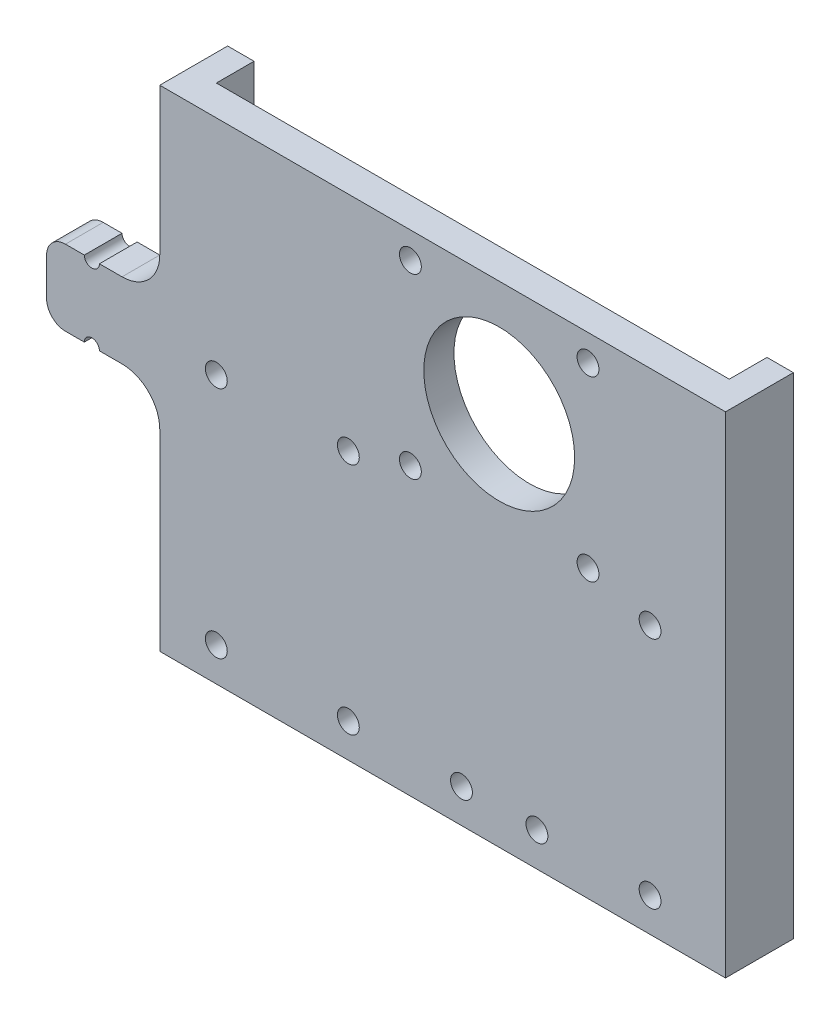
SolidWorks part; units mm, degrees
material "Acrylic (Medium-high impact)"
ref_plane "Front Plane" through (0, 0, 0) normal (0, 0, 1) x (1, 0, 0)
ref_plane "Top Plane" through (0, 0, 0) normal (0, 1, 0) x (1, 0, 0)
ref_plane "Right Plane" through (0, 0, 0) normal (1, 0, 0) x (0, 0, -1)
sketch "Sketch1" plane through (0, 0, 0) normal (0, 0, 1) x (1, 0, 0)
  line L1 (-50, 65) -> (50, 65)
  line L2 (-50, 65) -> (-50, -65)
  line L3 (-50, -65) -> (50, -65)
  line L4 (50, 65) -> (50, -65)
  line L5 (-50, 65) -> (50, -65) construction
  line L6 (-50, -65) -> (50, 65) construction
  point P0 (0, 0)
  dimension "D1" = 100
  dimension "D2" = 130
extrude "Boss-Extrude1" add sketch "Sketch1" along normal blind 8
sketch "Sketch4" plane through (0, 0, 8) normal (0, 0, 1) x (1, 0, 0)
  line L0 (-50, -65) -> (50, -65) construction
  line L1 (50, 65) -> (-50, 65) construction
  line L2 (-50, 65) -> (-50, -65) construction
  line L3 (50, -65) -> (50, 65) construction
  point P0 (-40, 6)
  point P2 (40, 6)
  point P4 (-40, -56)
  point P6 (40, -56)
  point P14 (-23.55, 58)
  point P16 (23.55, 58)
  point P17 (-23.55, 10.9)
  point P19 (23.55, 10.9)
  point P43 (-10, -56)
  point P46 (10, -56)
  dimension "D1" = 62
  dimension "D3" = 9
  dimension "D6" = 47.1
  dimension "D7" = 7
  dimension "D8" = 47.1
  dimension "D9" = 23.55
  dimension "D2" = 10
  dimension "D4" = 10
  dimension "D5" = 20
  dimension "D10" = 10
hole_wizard "M5 Clearance Hole1" positions "Sketch4" profile "Sketch3" hole size "M5" standard "ISO" end condition through all
sketch "Sketch3" plane through (-40, 6, 8) normal (1, 0, 0) x (0, -1, 0)
  line L0 (0, 0) -> (0, 8)
  line L1 (0, 8) -> (2.9, 8)
  line L2 (2.9, 8) -> (2.9, 0)
  line L5 (2.9, 0) -> (0, 0)
  line L11 (0, -6.35) -> (0, 107.95) construction
  dimension "Thru Hole Dia." = 5.8
  dimension "Thru Hole Depth" = 8
sketch "Sketch6" plane through (0, 0, 8) normal (0, 0, 1) x (1, 0, 0)
  circle A0 centre (0, 34.5) radius 20
  circle A1 centre (-23.55, 58) radius 2.9 construction
  dimension "D1" = 40
  dimension "D2" = 23.5
extrude "Cut-Extrude1" cut sketch "Sketch6" against normal blind 10
sketch "Sketch9" plane through (0, 0, 8) normal (0, 0, 1) x (1, 0, 0)
  line L0 (-50, -65) -> (50, -65) construction
  line L1 (-50, 65) -> (-90, 65)
  line L2 (-50, 65) -> (-50, -65)
  line L3 (-50, -65) -> (-90, -65)
  line L4 (-90, 65) -> (-90, -65)
  line L6 (50, 65) -> (60, 65)
  line L7 (50, 65) -> (50, -65)
  line L8 (50, -65) -> (60, -65)
  line L9 (60, 65) -> (60, -65)
  dimension "D1" = 40
  dimension "D2" = 10
extrude "Boss-Extrude2" add sketch "Sketch9" against normal up to surface (8 mm away) up to face at (20, 34.5, 0)
sketch "Sketch12" plane through (0, 0, 8) normal (0, 0, 1) x (1, 0, 0)
  point P0 (-75, 6)
  point P2 (-75, -56)
  dimension "D1" = 35
hole_wizard "M5 Clearance Hole2" positions "Sketch12" profile "Sketch11" hole size "M5" standard "ANSI Metric" end condition through all
sketch "Sketch11" plane through (-75, 6, 8) normal (1, 0, 0) x (0, -1, 0)
  line L0 (0, 0) -> (0, 8)
  line L1 (0, 8) -> (2.9, 8)
  line L2 (2.9, 8) -> (2.9, 0)
  line L5 (2.9, 0) -> (0, 0)
  line L11 (0, -6.35) -> (0, 107.95) construction
  dimension "Thru Hole Dia." = 5.8
  dimension "Thru Hole Depth" = 8
sketch "Sketch8" plane through (0, 0, 8) normal (0, 0, 1) x (1, 0, 0)
  line L0 (-50, -25) -> (50, -25) construction
  circle A1 centre (-40, 6) radius 2.9 construction
  dimension "D1" = 31
ref_plane "Plane1" through (0, -25, 0) normal (0, -1, 0) x (1, 0, 0)
sketch "Sketch13" plane through (0, 0, 0) normal (0, 0, -1) x (-1, 0, 0)
  line L0 (90, -65) -> (-60, -65) construction
  line L1 (-60, 65) -> (-53, 65)
  line L2 (-60, 65) -> (-60, -65)
  line L3 (-60, -65) -> (-53, -65)
  line L4 (-53, 65) -> (-53, -65)
  line L6 (90, 65) -> (83, 65)
  line L7 (90, 65) -> (90, -65)
  line L8 (90, -65) -> (83, -65)
  line L9 (83, 65) -> (83, -65)
  dimension "D1" = 7
  dimension "D2" = 7
extrude "Boss-Extrude3" add sketch "Sketch13" along normal blind 10
sketch "Sketch14" plane through (0, 0, 8) normal (0, 0, 1) x (1, 0, 0)
  line L0 (-90, 65) -> (-90, -65) construction
  line L1 (-90, 16) -> (-120, 16)
  line L2 (-90, 16) -> (-90, -4)
  line L3 (-90, -4) -> (-120, -4)
  line L4 (-120, 16) -> (-120, -4)
  point P6 (-90, 6)
  dimension "D1" = 20
  dimension "D2" = 30
extrude "Boss-Extrude4" add sketch "Sketch14" against normal blind 10
fillet "Fillet1" radius 10 2 edges at (-90, -4, 3) (-90, 16, 3)
fillet "Fillet2" radius 5 2 edges at (-120, 16, 3) (-120, -4, 3)
sketch "Sketch15" plane through (0, 0, -2) normal (0, 0, -1) x (-1, 0, 0)
  line L0 (106, 16) -> (110, 16)
  line L1 (100, 16) -> (115, 16) construction
  line L2 (110, -4) -> (106, -4)
  line L3 (115, -4) -> (100, -4) construction
  line L4 (120, 11) -> (120, 1) construction
  arc A0 (110, 16) -> (106, 16) centre (108, 16) cw
  arc A1 (106, -4) -> (110, -4) centre (108, -4) cw
  dimension "D1" = 2
  dimension "D2" = 12
extrude "Cut-Extrude2" cut sketch "Sketch15" against normal up to next
equation "\"Roller_Wheel_Gap\"=62"
equation "\"D1@Sketch4\"=\"Roller_Wheel_Gap\""
equation "\"D1@Sketch8\"=\"Roller_Wheel_Gap\"/2"
